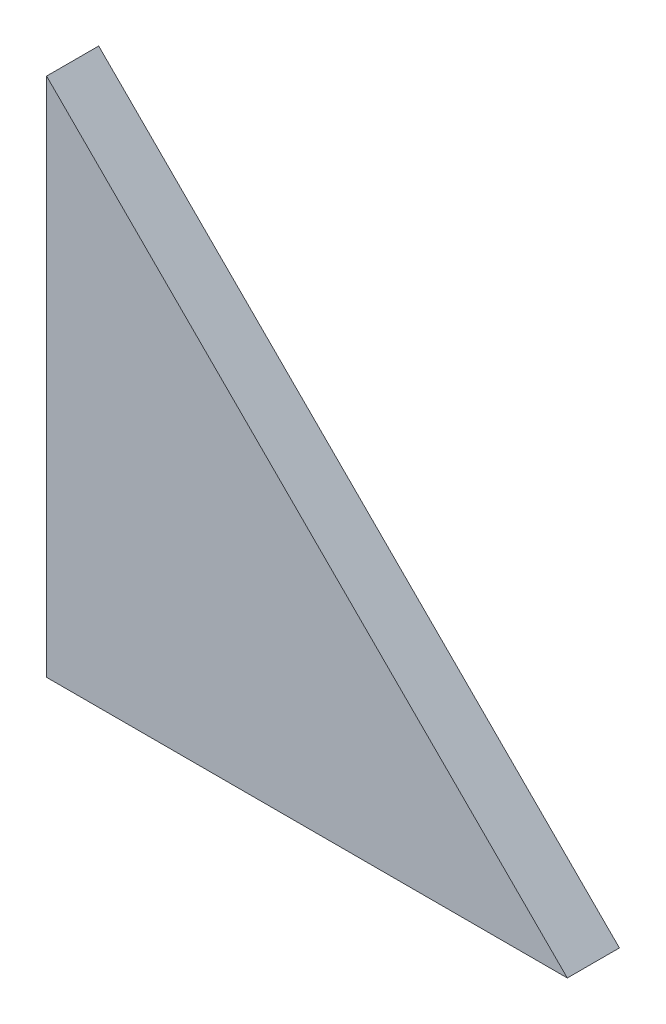
SolidWorks part; units mm, degrees
ref_plane "Ebene vorne" through (0, 0, 0) normal (0, 0, 1) x (1, 0, 0)
ref_plane "Ebene oben" through (0, 0, 0) normal (0, 1, 0) x (1, 0, 0)
ref_plane "Ebene rechts" through (0, 0, 0) normal (1, 0, 0) x (0, 0, -1)
sketch "Skizze1" plane through (0, 0, 0) normal (0, 0, 1) x (1, 0, 0)
  line L0 (0, 0) -> (0, 40)
  line L1 (0, 40) -> (40, 0)
  line L2 (40, 0) -> (0, 0)
  dimension "D1" = 40
extrude "Aufsatz-Linear austragen1" add sketch "Skizze1" along normal blind 4
